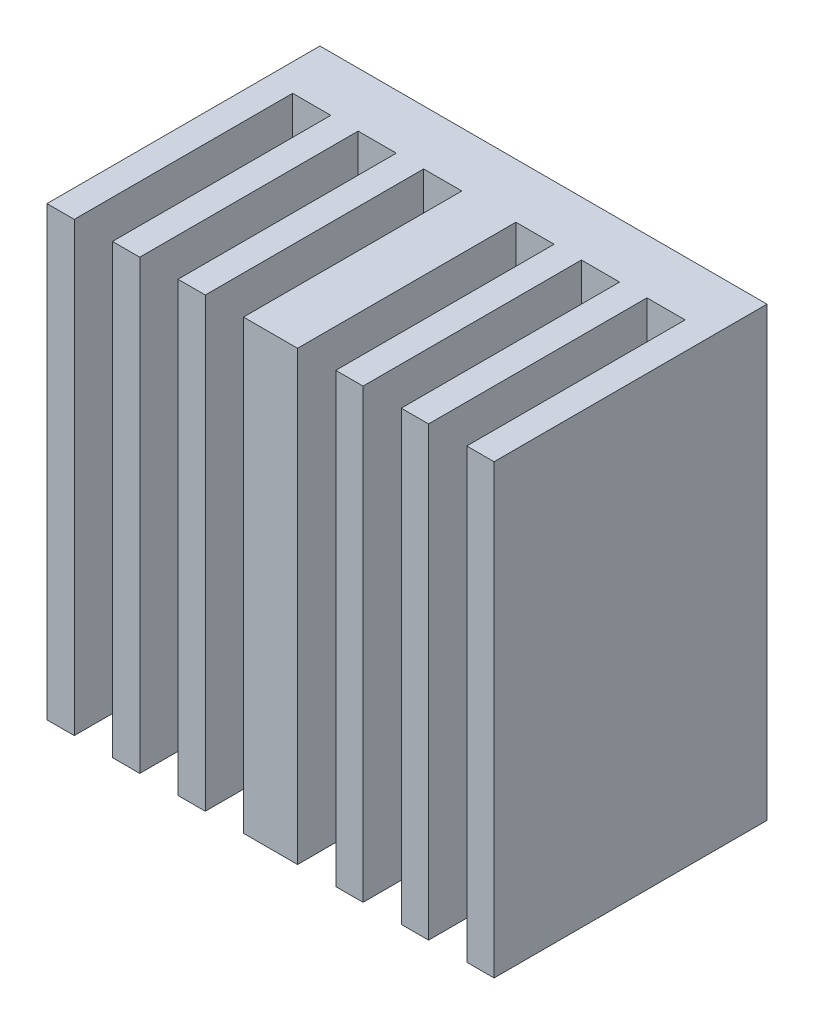
SolidWorks part; units mm, degrees
ref_plane "Plan de face" through (0, 0, 0) normal (0, 0, 1) x (1, 0, 0)
ref_plane "Plan de dessus" through (0, 0, 0) normal (0, 1, 0) x (1, 0, 0)
ref_plane "Plan de droite" through (0, 0, 0) normal (1, 0, 0) x (0, 0, -1)
sketch "Esquisse1" plane through (0, 0, 0) normal (0, 0, 1) x (1, 0, 0)
  line L1 (0, 0) -> (8.19, 0)
  line L2 (0, 0) -> (0, 8.19)
  line L3 (0, 8.19) -> (8.19, 8.19)
  line L4 (8.19, 0) -> (8.19, 8.19)
  dimension "D1" = 8.19
  dimension "D2" = 8.19
extrude "Boss.-Extru.1" add sketch "Esquisse1" along normal blind 5
sketch "Esquisse2" plane through (0, 0, 5) normal (0, 0, 1) x (1, 0, 0)
  line L0 (8.19, 8.19) -> (0, 8.19) construction
  line L1 (0.5, 8.19) -> (1.2, 8.19)
  line L2 (0.5, 8.19) -> (0.5, 0)
  line L3 (0.5, 0) -> (1.2, 0)
  line L4 (1.2, 8.19) -> (1.2, 0)
  line L5 (0, 0) -> (8.19, 0) construction
  line L6 (4.095, 8.19) -> (4.095, 0) construction
  line L7 (0, 8.19) -> (0, 0) construction
  line L8 (1.7, 8.19) -> (2.4, 8.19)
  line L9 (1.7, 8.19) -> (1.7, 0)
  line L10 (1.7, 0) -> (2.4, 0)
  line L11 (2.4, 8.19) -> (2.4, 0)
  line L12 (4.59, 8.19) -> (4.59, 0)
  line L13 (2.9, 8.19) -> (3.6, 8.19)
  line L14 (2.9, 8.19) -> (2.9, 0)
  line L15 (2.9, 0) -> (3.6, 0)
  line L16 (3.6, 8.19) -> (3.6, 0)
  line L17 (5.29, 0) -> (4.59, 0)
  line L18 (5.29, 8.19) -> (5.29, 0)
  line L19 (5.29, 8.19) -> (4.59, 8.19)
  line L20 (5.79, 8.19) -> (5.79, 0)
  line L21 (6.49, 0) -> (5.79, 0)
  line L22 (6.49, 8.19) -> (6.49, 0)
  line L23 (6.49, 8.19) -> (5.79, 8.19)
  line L24 (6.99, 8.19) -> (6.99, 0)
  line L25 (7.69, 0) -> (6.99, 0)
  line L26 (7.69, 8.19) -> (7.69, 0)
  line L27 (7.69, 8.19) -> (6.99, 8.19)
  dimension "D1" = 0.5
  dimension "D2" = 0.7
  dimension "D3" = 0.5
  dimension "D4" = 0.7
  dimension "D5" = 0.5
  dimension "D6" = 0.7
extrude "Enlèv. mat.-Extru.1" cut sketch "Esquisse2" against normal blind 4
